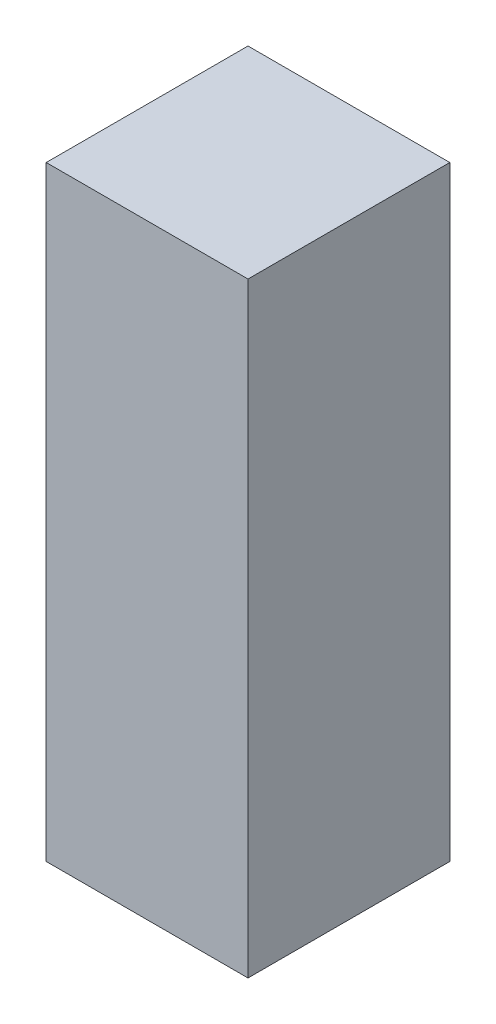
SolidWorks part; units mm, degrees
ref_plane "Front Plane" through (0, 0, 0) normal (0, 0, 1) x (1, 0, 0)
ref_plane "Top Plane" through (0, 0, 0) normal (0, 1, 0) x (1, 0, 0)
ref_plane "Right Plane" through (0, 0, 0) normal (1, 0, 0) x (0, 0, -1)
sketch "Sketch1" plane through (0, 0, 0) normal (0, 1, 0) x (1, 0, 0)
  line L1 (0, 0) -> (50.8, 0)
  line L2 (0, 0) -> (0, 50.8)
  line L3 (0, 50.8) -> (50.8, 50.8)
  line L4 (50.8, 0) -> (50.8, 50.8)
  dimension "D1" = 50.8
  dimension "D2" = 50.8
extrude "Boss-Extrude1" add sketch "Sketch1" along normal blind 152.4
